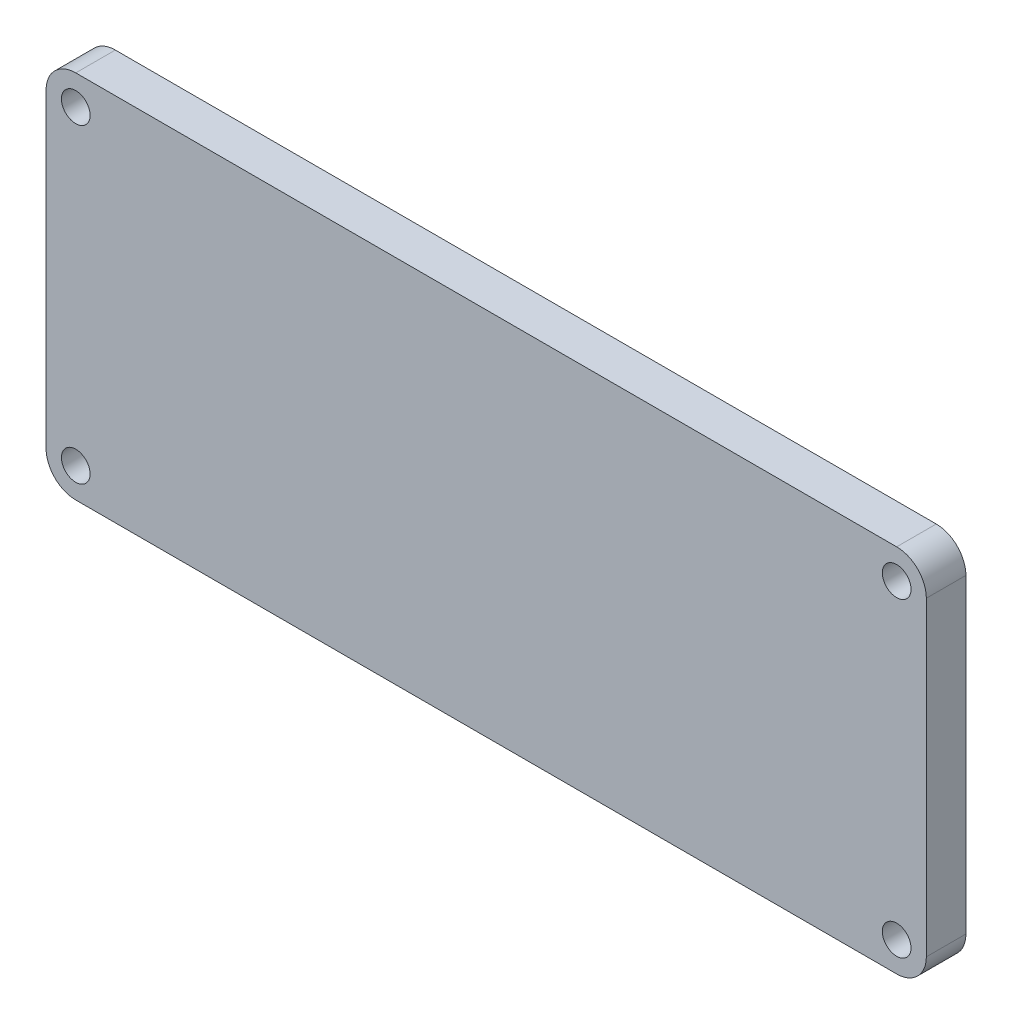
SolidWorks part; units mm, degrees
ref_plane "정면" through (0, 0, 0) normal (0, 0, 1) x (1, 0, 0)
ref_plane "윗면" through (0, 0, 0) normal (0, 1, 0) x (1, 0, 0)
ref_plane "우측면" through (0, 0, 0) normal (1, 0, 0) x (0, 0, -1)
sketch "스케치1" plane through (0, 0, 0) normal (0, 0, 1) x (1, 0, 0)
  line L0 (-44.5, 18.7) -> (44.5, 18.7)
  line L1 (-39.5, -13.7) -> (39.5, -13.7)
  line L2 (-39.5, -13.7) -> (-39.5, 13.7)
  line L3 (-39.5, 13.7) -> (39.5, 13.7)
  line L4 (39.5, -13.7) -> (39.5, 13.7)
  line L5 (-39.5, -13.7) -> (39.5, 13.7) construction
  line L6 (-39.5, 13.7) -> (39.5, -13.7) construction
  line L7 (44.5, -18.7) -> (44.5, 18.7)
  line L8 (-44.5, -18.7) -> (44.5, -18.7)
  line L9 (-44.5, -18.7) -> (-44.5, 18.7)
  point P0 (0, 0)
  dimension "D1" = 79
  dimension "D2" = 27.4
  dimension "D3" = 5
extrude "보스-돌출1" add sketch "스케치1" along normal blind 4 contours L0 L7 L8 L9
fillet "필렛1" radius 3 4 edges at (44.5, -18.7, 2) (-44.5, -18.7, 2) (44.5, 18.7, 2) (-44.5, 18.7, 2)
sketch "스케치2" plane through (0, 0, 0) normal (0, 0, 1) x (1, 0, 0)
  line L0 (0, 0) -> (-44.5, 0) construction
  line L1 (-44.5, -15.7) -> (-44.5, 15.7) construction
  line L2 (0, 0) -> (0, 18.7) construction
  line L3 (-41.5, 18.7) -> (41.5, 18.7) construction
  circle A0 centre (-41.5, 15.7) radius 1.45
  circle A1 centre (41.5, 15.7) radius 1.45
  circle A2 centre (41.5, -15.7) radius 1.45
  circle A3 centre (-41.5, -15.7) radius 1.45
  dimension "D1" = 2.9
extrude "컷-돌출3" cut sketch "스케치2" along normal blind 4
chamfer "모따기1" distance 1.2 distance2 1.5 4 edges at (-42.95, -15.7, 0) (-40.05, 15.7, 0) (42.95, -15.7, 0) (40.05, 15.7, 0)
